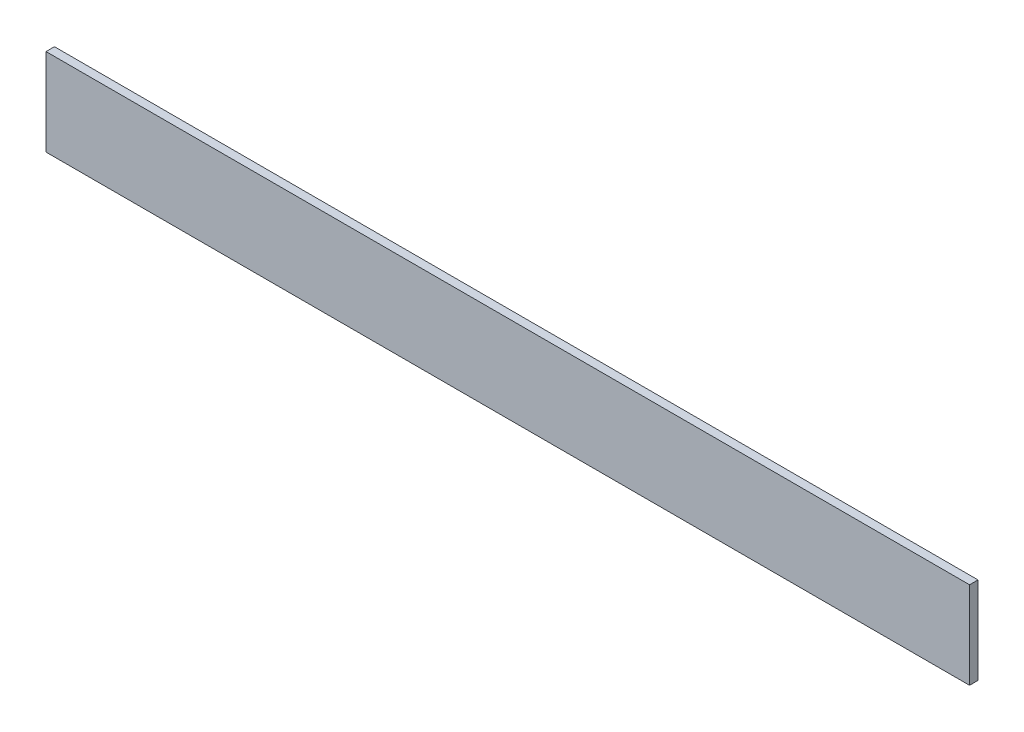
SolidWorks part; units mm, degrees
ref_plane "Front Plane" through (0, 0, 0) normal (0, 0, 1) x (1, 0, 0)
ref_plane "Top Plane" through (0, 0, 0) normal (0, 1, 0) x (1, 0, 0)
ref_plane "Right Plane" through (0, 0, 0) normal (1, 0, 0) x (0, 0, -1)
sketch "Sketch1" plane through (0, 0, 0) normal (0, 0, 1) x (1, 0, 0)
  line L1 (-87.5, 8.25) -> (87.5, 8.25)
  line L2 (-87.5, 8.25) -> (-87.5, -8.25)
  line L3 (-87.5, -8.25) -> (87.5, -8.25)
  line L4 (87.5, 8.25) -> (87.5, -8.25)
  line L5 (-87.5, 8.25) -> (87.5, -8.25) construction
  line L6 (-87.5, -8.25) -> (87.5, 8.25) construction
  point P0 (0, 0)
  dimension "D1" = 175
  dimension "D2" = 16.5
extrude "Boss-Extrude1" add sketch "Sketch1" along normal mid plane 1.6
